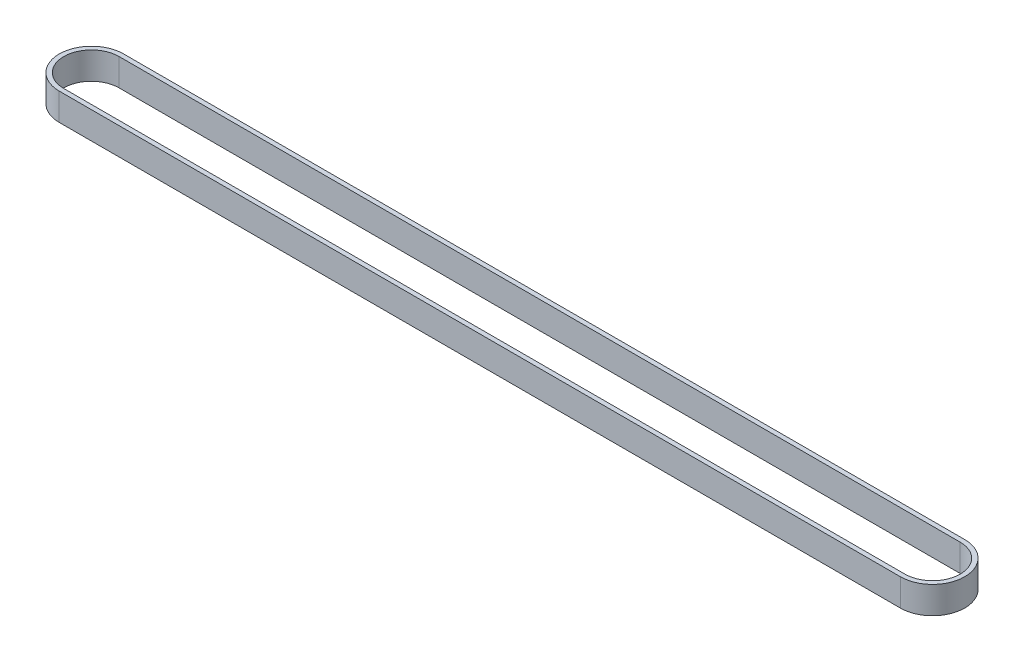
SolidWorks part; units mm, degrees
ref_plane "Front Plane" through (0, 0, 0) normal (0, 0, 1) x (1, 0, 0)
ref_plane "Top Plane" through (0, 0, 0) normal (0, 1, 0) x (1, 0, 0)
ref_plane "Right Plane" through (0, 0, 0) normal (1, 0, 0) x (0, 0, -1)
sketch "Sketch1" plane through (0, 0, 0) normal (0, 1, 0) x (1, 0, 0)
  line L0 (0, 6.1122) -> (185.7986, 6.1122)
  line L1 (0, -6.1122) -> (185.7986, -6.1122)
  line L2 (0, 0) -> (185.7986, 0) construction
  line L3 (92.8993, 0) -> (92.8993, 35.2448) construction
  line L4 (0, 7.11) -> (185.7986, 7.11)
  line L5 (0, -7.11) -> (185.7986, -7.11)
  arc A0 (0, 6.1122) -> (0, -6.1122) centre (0, 0) ccw
  arc A1 (185.7986, -6.1122) -> (185.7986, 6.1122) centre (185.7986, 0) ccw
  arc A2 (0, 7.11) -> (0, -7.11) centre (0, 0) ccw
  arc A3 (185.7986, 7.11) -> (185.7986, -7.11) centre (185.7986, 0) cw
  dimension "D1" = 12.2244
  dimension "D2" = 185.7986
  dimension "D3" = 14.22
extrude "Boss-Extrude1" add sketch "Sketch1" along normal blind 6
